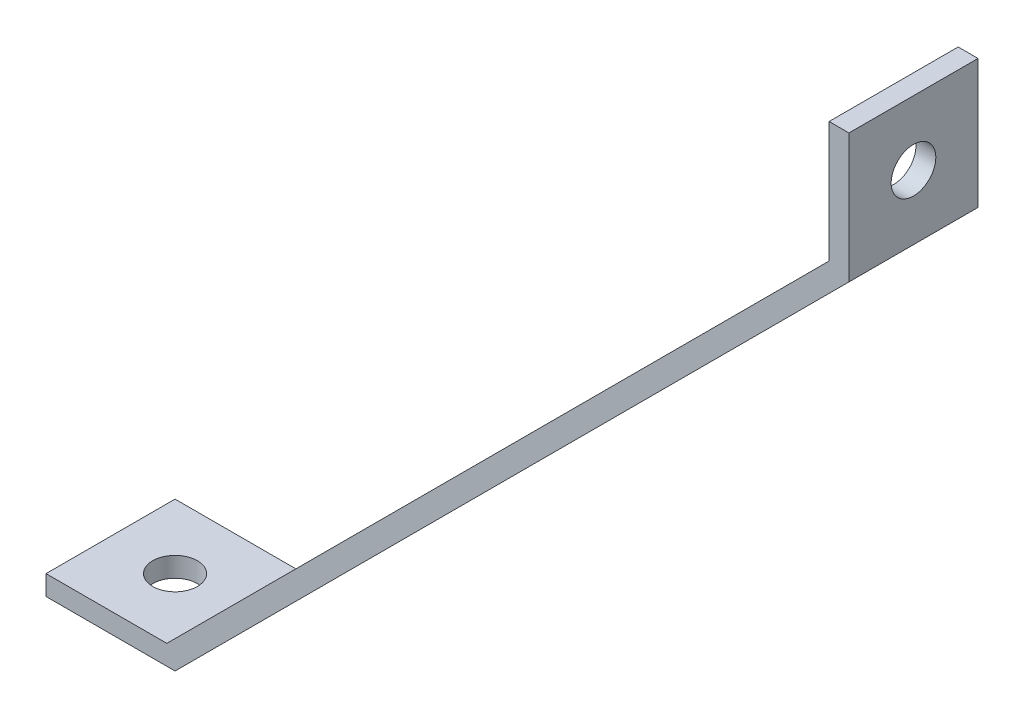
SolidWorks part; units mm, degrees
ref_plane "Front Plane" through (0, 0, 0) normal (0, 0, 1) x (1, 0, 0)
ref_plane "Top Plane" through (0, 0, 0) normal (0, 1, 0) x (1, 0, 0)
ref_plane "Right Plane" through (0, 0, 0) normal (1, 0, 0) x (0, 0, -1)
sketch "Sketch1" plane through (0, 0, 0) normal (0, 0, 1) x (1, 0, 0)
  line L0 (-149.0381, -107.7631) -> (-107.7631, -107.7631)
  line L1 (-107.7631, -107.7631) -> (107.7631, 107.7631)
  line L2 (107.7631, 107.7631) -> (107.7631, 149.0381)
  dimension "D1" = 45
  dimension "D2" = 41.275
  dimension "LG" = 304.8
extrude "Extrude-Thin1" add sketch "Sketch1" along normal mid plane 41.275 thin thin type one direction reverse wall 6.35
sketch "Sketch2" plane through (0, -101.4131, 0) normal (0, 1, 0) x (1, 0, 0)
  line L0 (-149.0381, -20.6375) -> (-149.0381, 20.6375) construction
  circle A0 centre (-128.4006, 0) radius 7.1438
  dimension "D1" = 14.2875
  dimension "D2" = 20.6375
extrude "Cut-Extrude1" cut sketch "Sketch2" against normal through all
sketch "Sketch3" plane through (101.4131, 0, 0) normal (-1, 0, 0) x (0, 0, 1)
  line L0 (20.6375, 149.0381) -> (-20.6375, 149.0381) construction
  circle A0 centre (0, 128.4006) radius 7.1437
  dimension "D1" = 14.2875
  dimension "D2" = 20.6375
extrude "Cut-Extrude2" cut sketch "Sketch3" against normal through all
